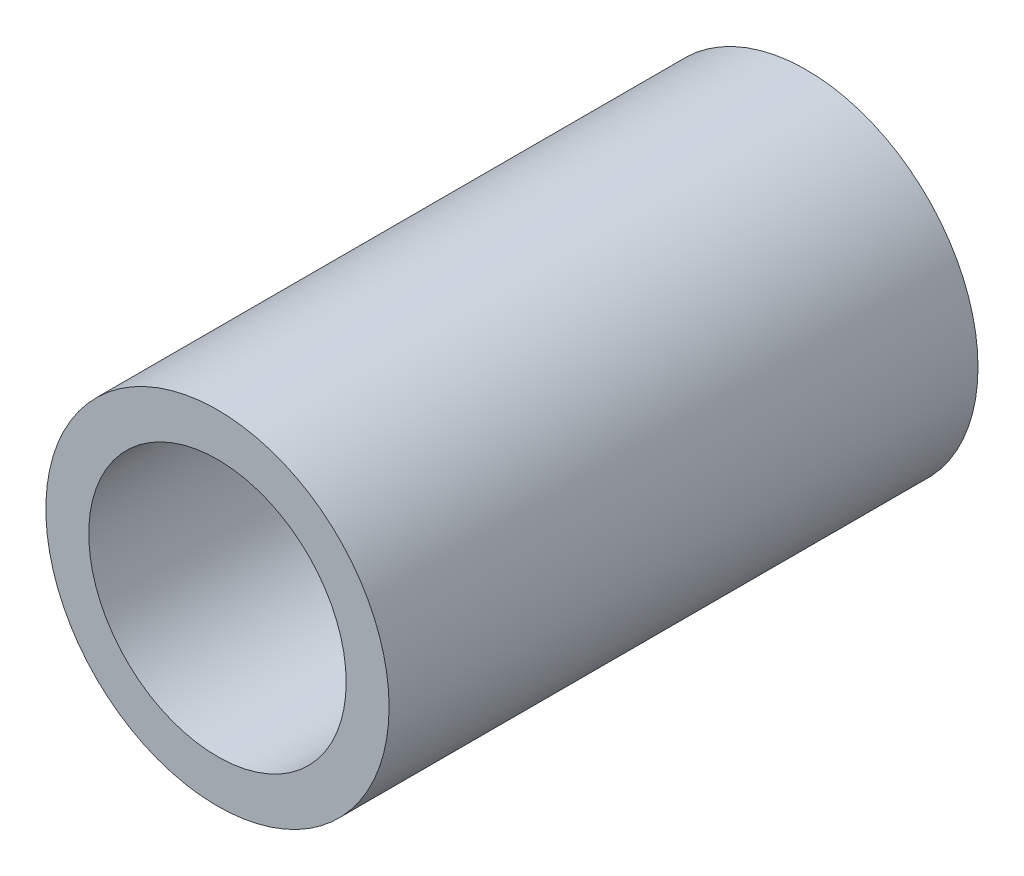
SolidWorks part; units mm, degrees
ref_plane "Plane1" through (0, 0, 0) normal (0, 0, 1) x (1, 0, 0)
ref_plane "Plane2" through (0, 0, 0) normal (0, 1, 0) x (1, 0, 0)
ref_plane "Plane3" through (0, 0, 0) normal (1, 0, 0) x (0, 0, -1)
sketch "Sketch1" plane through (0, 0, 0) normal (0, 0, 1) x (1, 0, 0)
  circle A0 centre (0, 0) radius 12.7
  dimension "D1" = 25.4
extrude "Base-Extrude" add sketch "Sketch1" along normal up to surface (28.575 mm away)
sketch "Sketch2" plane through (0, 0, 28.575) normal (0, 0, 1) x (1, 0, 0)
  circle A0 centre (0, 0) radius 9.525
  dimension "D1" = 19.05
extrude "Cut-Extrude1" cut sketch "Sketch2" against normal through all
sketch "Эскиз1" plane through (0, 0, 28.575) normal (0, 0, 1) x (1, 0, 0)
  circle A0 centre (0, 0) radius 9.525 construction
  circle A1 centre (0, 0) radius 12.7 construction
  circle A2 centre (0, 0) radius 9.525
  circle A3 centre (0, 0) radius 12.7
extrude "Бобышка-Вытянуть1" add sketch "Эскиз1" against normal blind 43.58
